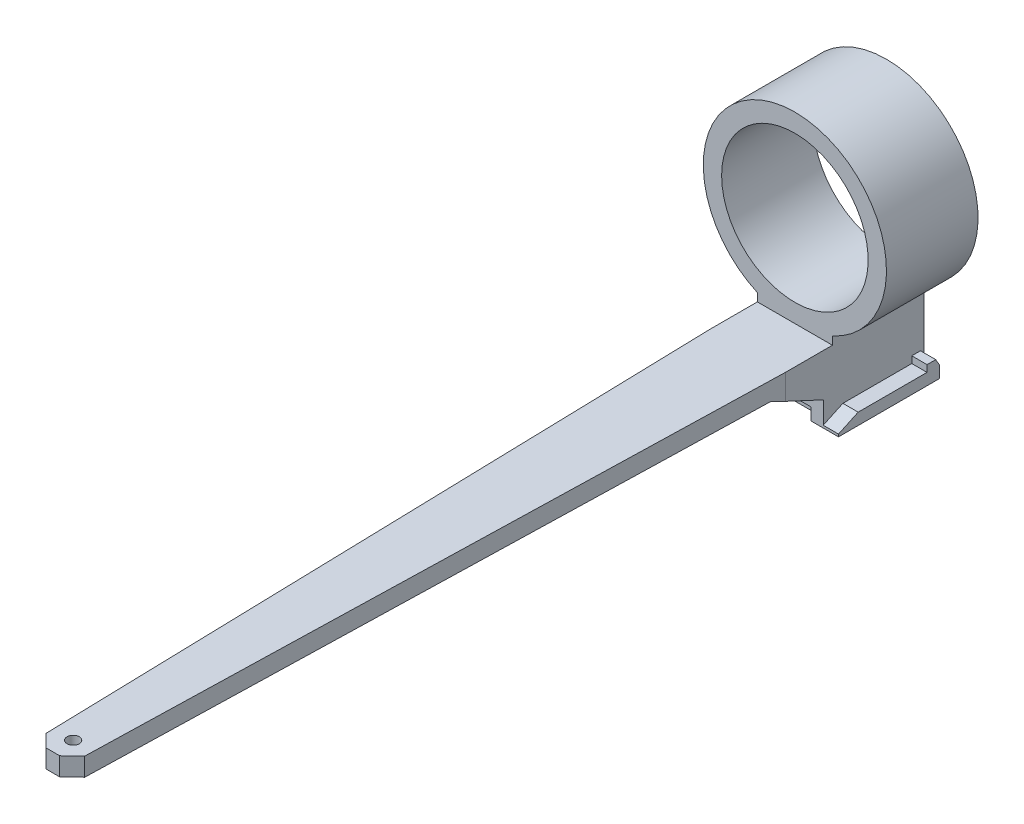
SolidWorks part; units mm, degrees
ref_plane "Front Plane" through (0, 0, 0) normal (0, 0, 1) x (1, 0, 0)
ref_plane "Top Plane" through (0, 0, 0) normal (0, 1, 0) x (1, 0, 0)
ref_plane "Right Plane" through (0, 0, 0) normal (1, 0, 0) x (0, 0, -1)
sketch "Sketch1" plane through (0, 0, 0) normal (0, 1, 0) x (1, 0, 0)
  line L1 (-16.7136, 15.7194) -> (0.7864, 15.7194)
  line L2 (-16.7136, 15.7194) -> (-16.7136, -0.7806)
  line L3 (-16.7136, -0.7806) -> (0.7864, -0.7806)
  line L4 (0.7864, 15.7194) -> (0.7864, -0.7806)
  dimension "D1" = 17.5
  dimension "D2" = 16.5
extrude "Boss-Extrude1" add sketch "Sketch1" along normal blind 3
sketch "Sketch2" plane through (0, 0, 0.7806) normal (0, 0, 1) x (1, 0, 0)
  line L0 (-16.7136, 0) -> (0.7864, 0) construction
  line L1 (-16.7136, 3) -> (-14.0066, 3)
  line L2 (-16.7136, 3) -> (-16.7136, 1.9)
  line L3 (-16.7136, 1.9) -> (-14.0066, 1.9)
  line L4 (-14.0066, 3) -> (-14.0066, 1.9)
  line L5 (0.7864, 3) -> (-1.7136, 3)
  line L6 (0.7864, 3) -> (0.7864, 1.9)
  line L7 (0.7864, 1.9) -> (-1.7136, 1.9)
  line L8 (-1.7136, 3) -> (-1.7136, 1.9)
  dimension "D1" = 1.9
  dimension "D2" = 1.9
  dimension "D3" = 2.5
extrude "Cut-Extrude1" cut sketch "Sketch2" against normal blind 14.5
chamfer "Chamfer1" distance 1.5 angle 65 2 edges at (-0.4636, 1.9, 0.7806) (-15.3601, 1.9, 0.7806)
chamfer "Chamfer2" distance 1 angle 30 1 edges at (-7.9636, 3, -15.7194)
sketch "Sketch3" plane through (0, 3, 0) normal (0, 1, 0) x (1, 0, 0)
  line L0 (0.7864, 15.142) -> (-16.7136, 15.142) construction
  line L1 (-14.0066, -0.7806) -> (-1.7136, -0.7806)
  line L2 (-14.0066, -0.7806) -> (-14.0066, 15.142)
  line L3 (-14.0066, 15.142) -> (-1.7136, 15.142)
  line L4 (-1.7136, -0.7806) -> (-1.7136, 15.142)
extrude "Boss-Extrude2" add sketch "Sketch3" along normal blind 8
sketch "Sketch4" plane through (0, 0, 0.7806) normal (0, 0, 1) x (1, 0, 0)
  line L0 (-1.7136, 11) -> (-1.7136, 0.4) construction
  line L1 (-14.0066, 11) -> (-1.7136, 11)
  line L2 (-14.0066, 11) -> (-14.0066, 8)
  line L3 (-14.0066, 8) -> (-1.7136, 8)
  line L4 (-1.7136, 11) -> (-1.7136, 8)
  dimension "D1" = 3
extrude "Boss-Extrude3" add sketch "Sketch4" along normal blind 120
chamfer "Chamfer3" distance 4 angle 65 1 edges
sketch "Sketch5" plane through (0, 11, 0) normal (0, 1, 0) x (1, 0, 0)
  line L0 (-16.7136, 15.7194) -> (0.7864, 15.7194) construction
  line L1 (-14.0066, 15.142) -> (-1.7136, 15.142)
  line L2 (-14.0066, 15.142) -> (-14.0066, 15.7194)
  line L3 (-14.0066, 15.7194) -> (-1.7136, 15.7194)
  line L4 (-1.7136, 15.142) -> (-1.7136, 15.7194)
extrude "Boss-Extrude4" add sketch "Sketch5" against normal blind 10
ref_plane "Plane1" through (0, 0, -15.7194) normal (0, 0, -1) x (-1, 0, 0)
sketch "Sketch6" plane through (0, 0, -15.7194) normal (0, 0, -1) x (-1, 0, 0)
  line L0 (1.7136, 11) -> (14.0066, 11) construction
  line L2 (1.7136, 11) -> (14.0066, 11)
  line L3 (1.7136, 11) -> (1.7136, 12.3171)
  line L5 (14.0066, 11) -> (14.0066, 12.3171)
  arc A0 (14.0066, 12.3171) -> (1.7136, 12.3171) centre (7.8601, 26) ccw
  circle A1 centre (7.8601, 26) radius 12
  dimension "D1" = 30
  dimension "D2" = 15
  dimension "D3" = 3
extrude "Boss-Extrude7" add sketch "Sketch6" against normal blind 15
sketch "Sketch7" plane through (0, 11, 0) normal (0, 1, 0) x (1, 0, 0)
  line L0 (-11.0066, -120.7806) -> (-14.0066, -6.9573)
  line L1 (-1.7136, -120.7806) -> (-14.0066, -120.7806) construction
  line L2 (-14.0066, 0.7194) -> (-14.0066, -120.7806) construction
  line L3 (-14.0066, -6.9573) -> (-14.0066, -120.7806)
  line L4 (-14.0066, -120.7806) -> (-11.0066, -120.7806)
  line L5 (-4.7136, -120.7806) -> (-1.7136, -120.7806)
  line L6 (-1.7136, -120.7806) -> (-1.7136, -6.9573)
  line L7 (-1.7136, -120.7806) -> (-1.7136, 0.7194) construction
  line L8 (-1.7136, -6.9573) -> (-4.7136, -120.7806)
  dimension "D1" = 3
  dimension "D2" = 3
extrude "Cut-Extrude3" cut sketch "Sketch7" against normal blind 15
sketch "Sketch10" plane through (0, 11, 0) normal (0, 1, 0) x (1, 0, 0)
  circle A0 centre (-7.8601, -117.4789) radius 1
  dimension "D1" = 2
extrude "Cut-Extrude4" cut sketch "Sketch10" against normal blind 15
chamfer "Chamfer5" distance 2 angle 45 2 edges at (-4.7136, 9.5, 120.7806) (-11.0066, 9.5, 120.7806)
sketch "Sketch11" plane through (0, 0, 0.7806) normal (0, 0, 1) x (1, 0, 0)
  line L0 (-16.7136, 0) -> (0.7864, 0) construction
  line L1 (-12.0066, 0) -> (-3.7136, 0)
  line L2 (-12.0066, 0) -> (-12.0066, 2)
  line L3 (-12.0066, 2) -> (-3.7136, 2)
  line L4 (-3.7136, 0) -> (-3.7136, 2)
  line L5 (-14.0066, 0.4) -> (-14.0066, 4) construction
  line L6 (-1.7136, 4) -> (-1.7136, 0.4) construction
  dimension "D1" = 2
  dimension "D2" = 2
  dimension "D3" = 2
extrude "Cut-Extrude5" cut sketch "Sketch11" against normal blind 1.5
equation "\"45g\"=30"
